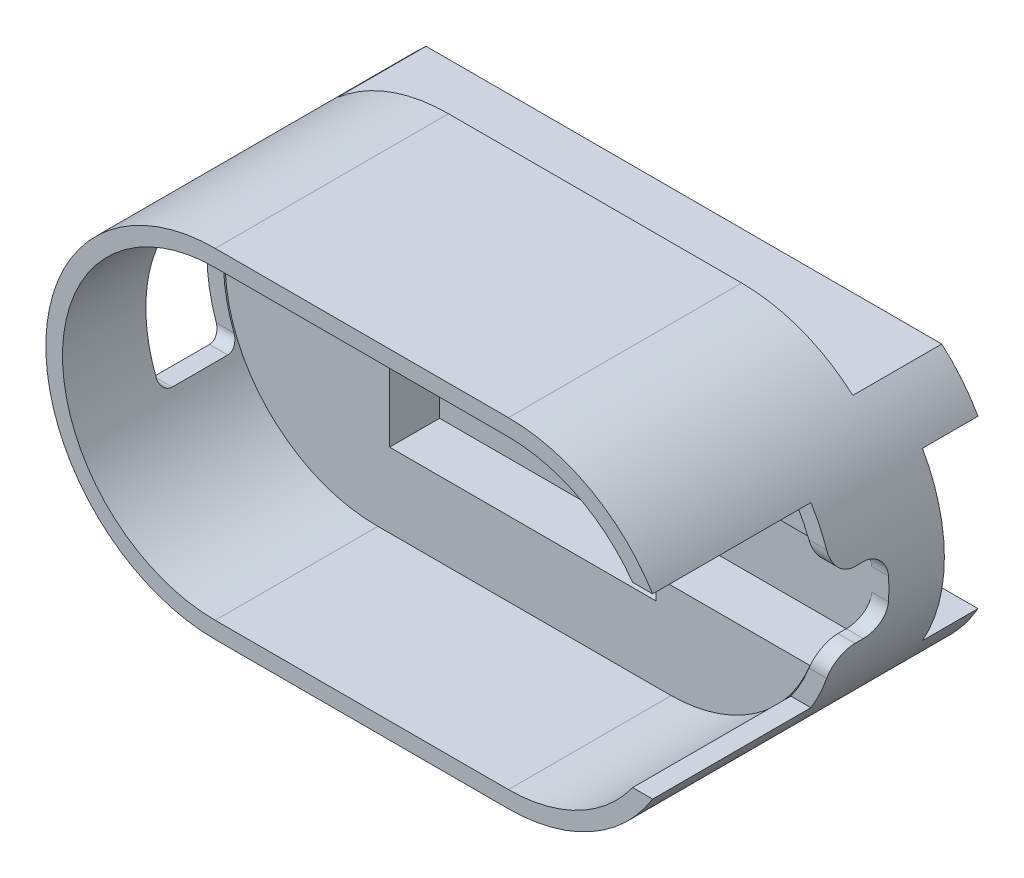
SolidWorks part; units mm, degrees
ref_plane "Front Plane" through (0, 0, 0) normal (0, 0, 1) x (1, 0, 0)
ref_plane "Top Plane" through (0, 0, 0) normal (0, 1, 0) x (1, 0, 0)
ref_plane "Right Plane" through (0, 0, 0) normal (1, 0, 0) x (0, 0, -1)
sketch "Sketch1" plane through (0, 0, 0) normal (0, 0, 1) x (1, 0, 0)
  line L0 (-34.3844, 17.2192) -> (-7.9844, 17.2192)
  line L1 (-34.3844, -10.2808) -> (-7.9844, -10.2808)
  line L2 (-34.3844, 18.7192) -> (-7.9844, 18.7192)
  line L3 (-34.3844, -11.7808) -> (-7.9844, -11.7808)
  arc A0 (-34.3844, 17.2192) -> (-34.3844, -10.2808) centre (-34.3844, 3.4692) ccw
  arc A1 (-7.9844, -10.2808) -> (-7.9844, 17.2192) centre (-7.9844, 3.4692) ccw
  arc A2 (-7.9844, -11.7808) -> (-7.9844, 18.7192) centre (-7.9844, 3.4692) ccw
  arc A3 (-34.3844, 18.7192) -> (-34.3844, -11.7808) centre (-34.3844, 3.4692) ccw
  point P8 (-48.1344, 3.4692)
  point P9 (5.7656, 3.4692)
  dimension "D1" = 27.5
  dimension "D2" = 53.9
  dimension "D3" = 1.5
extrude "Boss-Extrude1" add sketch "Sketch1" along normal blind 19
sketch "Sketch2" plane through (0, 0, 0) normal (0, 0, -1) x (-1, 0, 0)
  line L0 (34.3844, -11.7808) -> (7.9844, -11.7808)
  line L1 (34.3844, 18.7192) -> (7.9844, 18.7192)
  arc A0 (7.9844, 18.7192) -> (7.9844, -11.7808) centre (7.9844, 3.4692) ccw
  arc A1 (34.3844, -11.7808) -> (34.3844, 18.7192) centre (34.3844, 3.4692) ccw
  arc M5 (34.3844, 17.2192) -> (34.3844, -10.2808) centre (34.3844, 3.4692) cw
  line M6 (34.3844, -10.2808) -> (7.9844, -10.2808)
  arc M7 (7.9844, -10.2808) -> (7.9844, 17.2192) centre (7.9844, 3.4692) cw
  line M8 (7.9844, 17.2192) -> (34.3844, 17.2192)
extrude "Boss-Extrude2" add sketch "Sketch2" along normal blind 2 separate body contours A1 A0 M8 M7 M6 | A1 A0 M6 | A1 A0 M8 M6 M5 | A0 A1 | A1 A0 M8
sketch "Sketch3" plane through (0, 0, 0) normal (0, 0, 1) x (1, 0, 0)
  line L0 (-21.1844, 17.2192) -> (-21.1844, -10.2808) construction
  line L1 (-7.9844, 17.2192) -> (-34.3844, 17.2192) construction
  line L2 (-34.3844, -10.2808) -> (-7.9844, -10.2808) construction
  line L3 (-9.1844, 3.4692) -> (4.8328, 3.4692) construction
  line L4 (-33.1844, -3.4308) -> (-9.1844, -3.4308)
  line L5 (-33.1844, -3.4308) -> (-33.1844, 10.3692)
  line L6 (-33.1844, 10.3692) -> (-9.1844, 10.3692)
  line L7 (-9.1844, -3.4308) -> (-9.1844, 10.3692)
  line L8 (-33.1844, -3.4308) -> (-9.1844, 10.3692) construction
  line L9 (-33.1844, 10.3692) -> (-9.1844, -3.4308) construction
  line L10 (-9.1844, -1.5308) -> (4.6632, -1.5308)
  line L11 (-9.1844, 8.4692) -> (4.6632, 8.4692)
  line L12 (-34.3844, 17.0693) -> (-7.9844, 17.0693)
  line L13 (-7.9844, -10.1309) -> (-34.3844, -10.1309)
  line L14 (-9.1844, -1.5308) -> (4.8328, -1.5308) construction
  line L15 (-9.1844, 8.4692) -> (4.8328, 8.4692) construction
  arc A0 (-19.7042, 10.3692) -> (-19.7042, -3.4308) centre (-7.9844, 3.4692) ccw
  arc A1 (-34.3844, 17.0693) -> (-34.3844, -10.1309) centre (-34.3844, 3.4692) ccw
  arc A2 (-7.9844, -10.1309) -> (-7.9844, 17.0693) centre (-7.9844, 3.4692) ccw
  arc A3 (-22.6647, -3.4308) -> (-21.1844, 6.7437) centre (-34.3844, 3.4692) ccw
  point P6 (-21.1844, 3.4692)
  dimension "D1" = 13.8
  dimension "D2" = 24
  dimension "D3" = 5
  dimension "D4" = 5
extrude "Boss-Extrude3" add sketch "Sketch3" along normal blind 4.5 contours L11 A2 L12 A1 L13 L10 L7 L4 L5 L6
sketch "Sketch4" plane through (-9.1844, 0, 0) normal (-1, 0, 0) x (0, 0, 1)
  line L0 (4.5, -1.5308) -> (4.5, 8.4692) construction
  line L1 (4.5, 3.4692) -> (9.0795, 3.4692) construction
  line L2 (0, -3.4308) -> (0, -1.5308) construction
  line L3 (4.75, 11.4692) -> (19, 11.4692)
  line L4 (4.75, 11.4692) -> (4.75, -4.5308)
  line L5 (4.75, -4.5308) -> (19, -4.5308)
  line L6 (19, 11.4692) -> (19, -4.5308)
  line L7 (4.75, 11.4692) -> (19, -4.5308) construction
  line L8 (4.75, -4.5308) -> (19, 11.4692) construction
  line L9 (0, 6.4692) -> (4.75, 6.4692)
  line L10 (0, 6.4692) -> (0, 0.4692)
  line L11 (0, 0.4692) -> (4.75, 0.4692)
  line L12 (4.75, 6.4692) -> (4.75, 0.4692)
  line L13 (0, 6.4692) -> (4.75, 0.4692) construction
  line L14 (0, 0.4692) -> (4.75, 6.4692) construction
  line L15 (19, -10.2808) -> (19, 17.2192) construction
  point P6 (11.875, 3.4692)
  point P11 (2.375, 3.4692)
  dimension "D1" = 16
  dimension "D3" = 0.5
  dimension "D4" = 6
extrude "Cut-Extrude1" cut sketch "Sketch4" against normal through all contours L10 L11 L4 L9 | L6 L3 L4 L5
sketch "Sketch5" plane through (-33.1844, 0, 0) normal (1, 0, 0) x (0, 0, -1)
  line L0 (-4.5, 3.4692) -> (-8.318, 3.4692) construction
  line L1 (-4.5, -3.4308) -> (-4.5, 10.3692) construction
  line L3 (-4.5, -2.5308) -> (-11.5, -2.5308)
  line L4 (-4.5, -2.5308) -> (-4.5, 9.4692)
  line L5 (-4.5, 9.4692) -> (-11.5, 9.4692)
  line L6 (-11.5, -2.5308) -> (-11.5, 9.4692)
  line L7 (-4.5, -2.5308) -> (-11.5, 9.4692) construction
  line L8 (-4.5, 9.4692) -> (-11.5, -2.5308) construction
  point P4 (-8, 3.4692)
  dimension "D1" = 12
  dimension "D2" = 7
extrude "Cut-Extrude2" cut sketch "Sketch5" against normal through all
fillet "Fillet1" radius 1 4 edges at (-47.5804, 9.4692, 4.5) (-47.5804, -2.5308, 4.5) (-47.5804, -2.5308, 11.5) (-47.5804, 9.4692, 11.5)
sketch "Sketch6" plane through (0, 0, -2) normal (0, 0, -1) x (-1, 0, 0)
  line L0 (49.6344, 3.4692) -> (-7.2656, 3.4692) construction
  line L1 (47.6627, 10.9692) -> (-5.2938, 10.9692)
  line L2 (47.6627, -4.0308) -> (-5.2938, -4.0308)
  line L3 (43.1201, -9.0308) -> (-0.7513, -9.0308)
  line L4 (43.1201, 15.9692) -> (-0.7513, 15.9692)
  line L5 (49.6344, -9.0308) -> (-7.2656, -9.0308) construction
  line L6 (49.6344, -4.0308) -> (-7.2656, -4.0308) construction
  line L7 (49.6344, 15.9692) -> (-7.2656, 15.9692) construction
  line L8 (49.6344, 10.9692) -> (-7.2656, 10.9692) construction
  arc A0 (34.3844, -11.7808) -> (34.3844, 18.7192) centre (34.3844, 3.4692) ccw construction
  arc A1 (7.9844, 18.7192) -> (7.9844, -11.7808) centre (7.9844, 3.4692) ccw construction
  arc A2 (43.1201, -9.0308) -> (43.1201, 15.9692) centre (34.3844, 3.4692) ccw
  arc A3 (21.1844, -4.1677) -> (21.1844, 11.1061) centre (7.9844, 3.4692) ccw
  arc A4 (-0.7513, 15.9692) -> (-0.7513, -9.0308) centre (7.9844, 3.4692) ccw
  arc A5 (21.1844, 11.1061) -> (21.1844, -4.1677) centre (34.3844, 3.4692) ccw
  circle A6 centre (21.1844, 3.4692) radius 1.6
  arc M5 (34.3844, -11.7808) -> (34.3844, 18.7192) centre (34.3844, 3.4692) ccw
  arc M7 (7.9844, 18.7192) -> (7.9844, -11.7808) centre (7.9844, 3.4692) ccw
  dimension "D5" = 3.2
  dimension "D1" = 7.5
  dimension "D2" = 7.5
  dimension "D3" = 5
  dimension "D4" = 5
extrude "Boss-Extrude4" add sketch "Sketch6" along normal blind 3 contours A3 L2 L1 M5 | L1 A5 L2 A3 | A5 L1 L2 M7
sketch "Sketch9" plane through (0, 0, -2) normal (0, 0, -1) x (-1, 0, 0)
  circle A0 centre (21.1844, 3.4692) radius 1.6
  circle A1 centre (21.1844, 3.4692) radius 1.6 construction
sketch "Sketch10" plane through (0, 0, -2) normal (0, 0, -1) x (-1, 0, 0)
  line L0 (-5.2938, -4.0308) -> (47.6627, -4.0308)
  line L1 (47.6627, 10.9692) -> (-5.2938, 10.9692)
  line L2 (44.4001, 14.9692) -> (-2.0312, 14.9692)
  line L3 (-2.0312, -8.0308) -> (44.4001, -8.0308)
  line L4 (-5.2938, -8.0308) -> (47.6627, -8.0308) construction
  line L5 (47.6627, 14.9692) -> (-5.2938, 14.9692) construction
  line L6 (47.6627, 10.9692) -> (-5.2938, 10.9692) construction
  arc A0 (44.4001, -8.0308) -> (47.6627, -4.0308) centre (34.3844, 3.4692) ccw
  arc A1 (47.6627, 10.9692) -> (44.4001, 14.9692) centre (34.3844, 3.4692) ccw
  arc A2 (-2.0312, 14.9692) -> (-5.2938, 10.9692) centre (7.9844, 3.4692) ccw
  arc A3 (-5.2938, -4.0308) -> (-2.0312, -8.0308) centre (7.9844, 3.4692) ccw
  line M2 (-5.2938, 10.9692) -> (47.6627, 10.9692)
  arc M3 (47.6627, 10.9692) -> (34.3844, 18.7192) centre (34.3844, 3.4692) ccw
  arc M5 (7.9844, 18.7192) -> (-5.2938, 10.9692) centre (7.9844, 3.4692) ccw
  dimension "D1" = 4
  dimension "D2" = 4
extrude "Boss-Extrude7" add sketch "Sketch10" along direction (0, 0, -1) on the side of the normal blind 8 contours L0 A3 L3 A0 | L2 M3 M5 M2
fillet "Fillet2" radius 2 4 edges at (6.2009, 0.4692, 0) (6.2009, 6.4692, 0) (6.2009, 6.4692, 4.75) (6.2009, 0.4692, 4.75)
extrude "Cut-Extrude3" cut sketch "Sketch9" against normal blind 10
sketch "Sketch11" plane through (0, 0, 0) normal (0, 0, 1) x (1, 0, 0)
  circle A0 centre (-21.1844, 3.4692) radius 2.065
  dimension "D1" = 4.13
extrude "Cut-Extrude4" cut sketch "Sketch11" against normal blind 3 from offset 1
